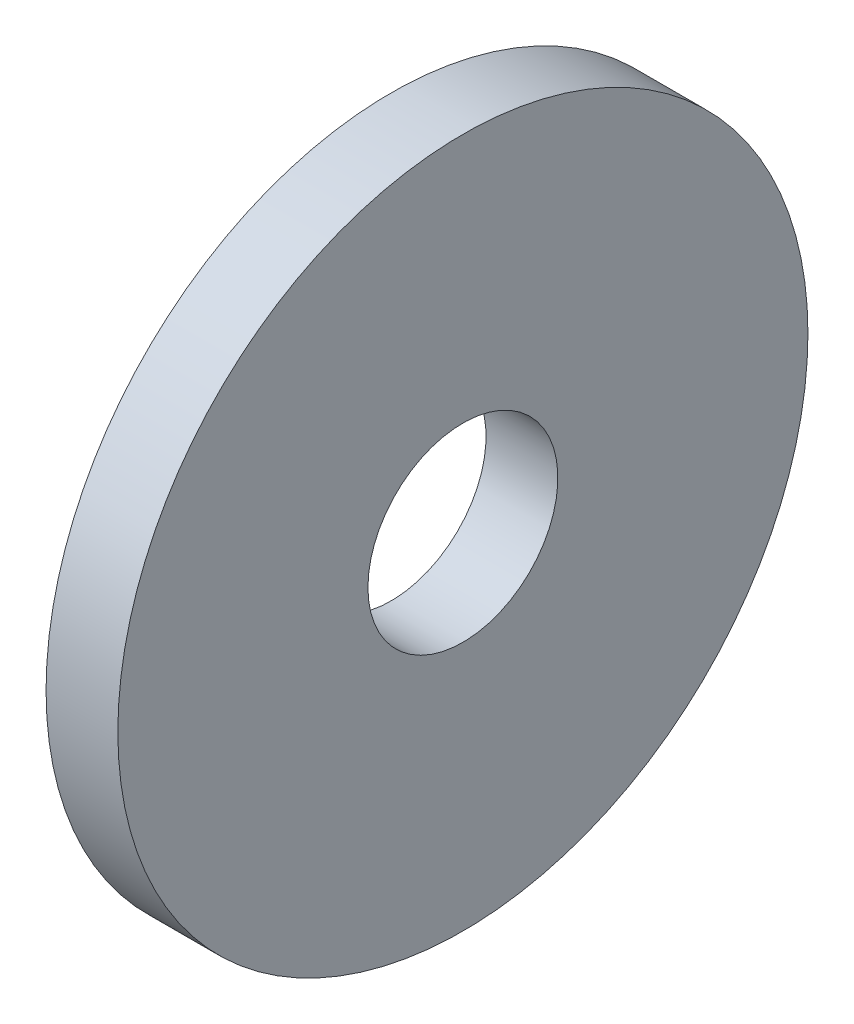
SolidWorks part; units mm, degrees
ref_plane "Front Plane" through (0, 0, 0) normal (0, 0, 1) x (1, 0, 0)
ref_plane "Top Plane" through (0, 0, 0) normal (0, 1, 0) x (1, 0, 0)
ref_plane "Right Plane" through (0, 0, 0) normal (1, 0, 0) x (0, 0, -1)
sketch "Sketch1" plane through (0, 0, 0) normal (1, 0, 0) x (0, 0, -1)
  circle A0 centre (0, 0) radius 15.875
  circle A1 centre (0, 0) radius 4.3688
  dimension "OD" = 31.75
  dimension "ID" = 8.7376
extrude "Boss-Extrude1" add sketch "Sketch1" along normal blind 3.302
